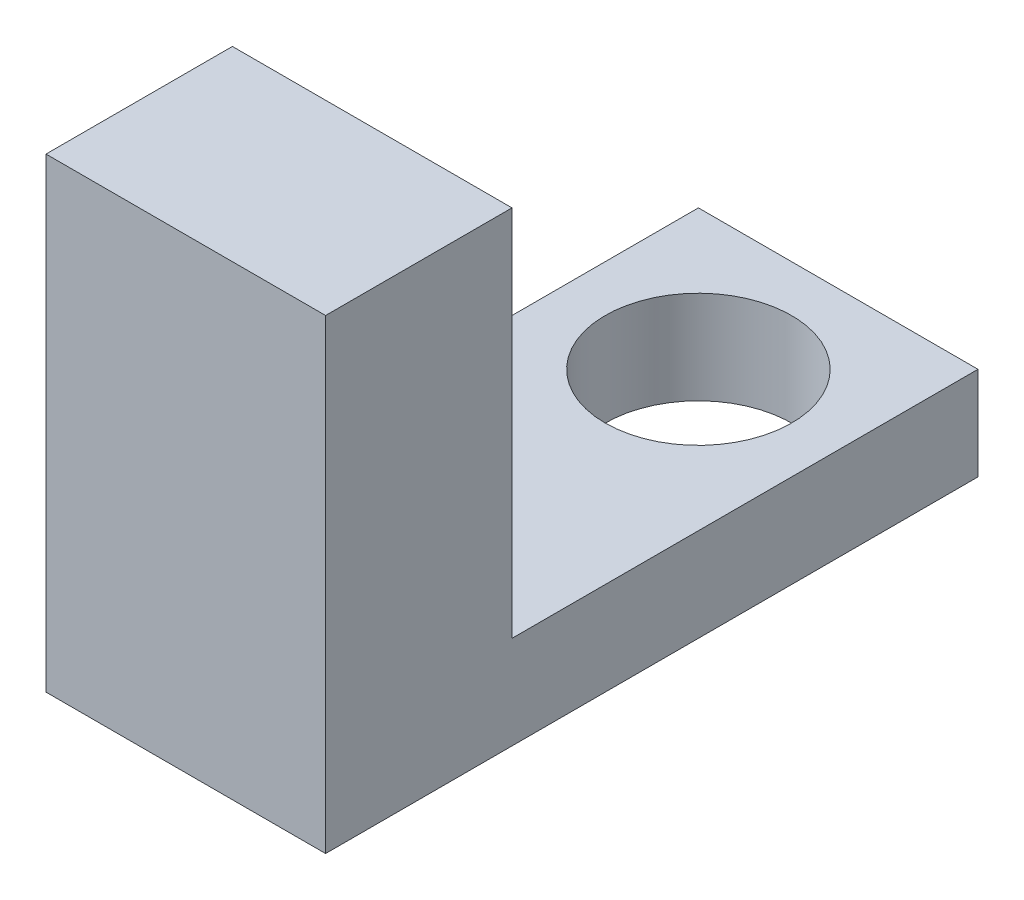
SolidWorks part; units mm, degrees
ref_plane "Front Plane" through (0, 0, 0) normal (0, 0, 1) x (1, 0, 0)
ref_plane "Top Plane" through (0, 0, 0) normal (0, 1, 0) x (1, 0, 0)
ref_plane "Right Plane" through (0, 0, 0) normal (1, 0, 0) x (0, 0, -1)
sketch "Sketch1" plane through (0, 0, 0) normal (1, 0, 0) x (0, 0, -1)
  line L0 (0, 40) -> (0, 0)
  line L1 (0, 0) -> (50, 0)
  line L2 (50, 0) -> (50, -10)
  line L3 (50, -10) -> (-20, -10)
  line L4 (-20, -10) -> (-20, 40)
  line L5 (-20, 40) -> (0, 40)
  dimension "D1" = 10
  dimension "D2" = 50
  dimension "D3" = 70
  dimension "D4" = 50
extrude "Boss-Extrude1" add sketch "Sketch1" along normal blind 30
sketch "Sketch2" plane through (0, 0, 0) normal (0, 1, 0) x (1, 0, 0)
  line L0 (30, 50) -> (30, 0) construction
  line L1 (30, 50) -> (0, 50) construction
  circle A0 centre (15, 35) radius 10
  dimension "D1" = 20
  dimension "D2" = 15
  dimension "D3" = 15
extrude "Cut-Extrude1" cut sketch "Sketch2" against normal blind 10
